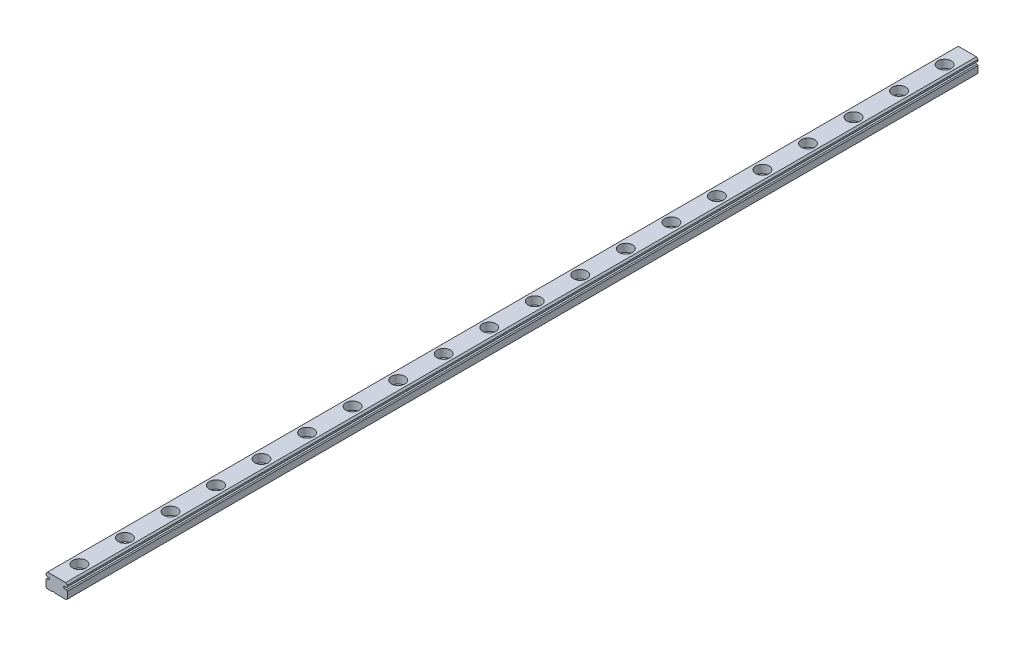
SolidWorks part; units mm, degrees
ref_plane "Front Plane" through (0, 0, 0) normal (0, 0, 1) x (1, 0, 0)
ref_plane "Top Plane" through (0, 0, 0) normal (0, 1, 0) x (1, 0, 0)
ref_plane "Right Plane" through (0, 0, 0) normal (1, 0, 0) x (0, 0, -1)
sketch "Sketch3" plane through (0, 0, 0) normal (0, 0, 1) x (1, 0, 0)
  line L0 (-3.5, 0) -> (-1.35, 0)
  line L1 (0, 0) -> (0, 4.8) construction
  line L2 (-3.5, 4.8) -> (3.5, 4.8)
  line L3 (-3.5, 0) -> (-3.5, 2.83)
  line L4 (3.5, 4.8) -> (3.5, 3.5)
  line L5 (-3.5, 3.5) -> (-2.65, 3.5)
  line L6 (-2.65, 3.5) -> (-2.65, 2.83) construction
  line L7 (-2.65, 2.83) -> (-3.5, 2.83)
  line L8 (-3.5, 3.5) -> (-3.5, 4.8)
  line L9 (2.65, 3.5) -> (2.65, 2.83) construction
  line L10 (2.65, 2.83) -> (3.5, 2.83)
  line L11 (3.5, 3.5) -> (2.65, 3.5)
  line L12 (3.5, 2.83) -> (3.5, 0)
  line L13 (-0.65, 0) -> (3.5, 0)
  arc A0 (-2.65, 3.5) -> (-2.65, 2.83) centre (-2.65, 3.165) cw
  arc A1 (2.65, 3.5) -> (2.65, 2.83) centre (2.65, 3.165) ccw
  arc A2 (-1.35, 0) -> (-0.65, 0) centre (-1, -0.3571) cw
  point P8 (0, 4.8)
  dimension "D8" = 0.5
  dimension "D1" = 7
  dimension "D2" = 4.8
  dimension "D3" = 1.3
  dimension "D4" = 2.65
  dimension "D5" = 0.67
  dimension "D6" = 1
  dimension "D7" = 0.7
extrude "Boss-Extrude1" add sketch "Sketch3" along normal mid plane 300
chamfer "Chamfer1" distance 0.5 angle 45 2 edges at (3.5, 4.8, 0) (-3.5, 4.8, 0)
chamfer "Chamfer2" distance 0.3 angle 45 6 edges at (3.5, 0, 0) (-3.5, 0, 0) (-3.5, 2.83, 0) (3.5, 2.83, 0) (3.5, 3.5, 0) (-3.5, 3.5, 0)
hole_wizard "CBORE for M2 SHCS1" positions "Sketch4" profile "Sketch5" counterbore size "M2" standard "ANSI Metric" end condition up to next
sketch "Sketch4" plane through (0, 4.8, 0) normal (0, 1, 0) x (1, 0, 0)
  line L0 (3, -150) -> (-3, -150) construction
  point P0 (0, -142.5)
  dimension "D1" = 7.5
sketch "Sketch5" plane through (0, 4.8, 142.5) normal (1, 0, 0) x (0, 0, 1)
  line L0 (0, 0) -> (0, 4.8)
  line L1 (0, 4.8) -> (1.2, 4.8)
  line L3 (1.2, 4.8) -> (1.2, 2.65)
  line L4 (1.2, 2.65) -> (2.2, 2.65)
  line L5 (2.2, 2.65) -> (2.2, 0)
  line L7 (2.2, 0) -> (0, 0)
  line L11 (0, -6.35) -> (0, 107.95) construction
  dimension "Thru Hole Dia." = 2.4
  dimension "Thru Hole Depth" = 4.8
  dimension "C'Bore Dia." = 4.4
  dimension "C'Bore Depth" = 2.65
pattern_linear "LPattern1" count 20 spacing 15 along (0, 0, -1) of "CBORE for M2 SHCS1"
